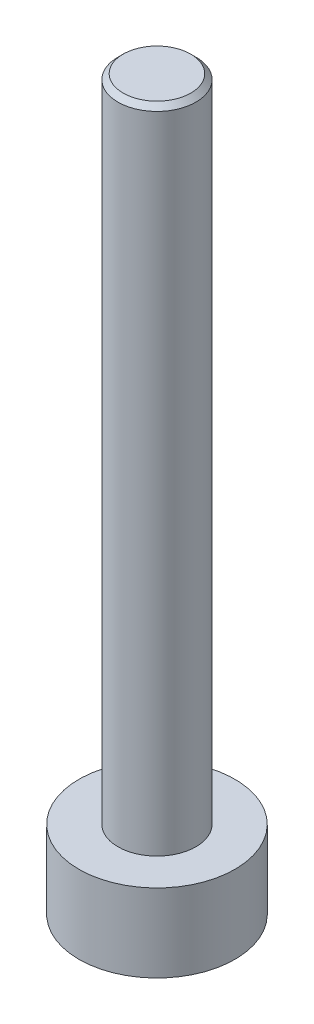
SolidWorks part; units mm, degrees
ref_plane "Front Plane" through (0, 0, 0) normal (0, 0, 1) x (1, 0, 0)
ref_plane "Top Plane" through (0, 0, 0) normal (0, 1, 0) x (1, 0, 0)
ref_plane "Right Plane" through (0, 0, 0) normal (1, 0, 0) x (0, 0, -1)
sketch "Sketch1" plane through (0, 0, 0) normal (0, 1, 0) x (1, 0, 0)
  circle A0 centre (0, 0) radius 3
  dimension "D1" = 6
extrude "Boss-Extrude1" add sketch "Sketch1" along normal blind 3
sketch "Sketch2" plane through (0, 3, 0) normal (0, 1, 0) x (1, 0, 0)
  circle A0 centre (0, 0) radius 1.5
  dimension "D1" = 3
extrude "Boss-Extrude2" add sketch "Sketch2" along normal blind 25 contours A0
chamfer "Chamfer1" distance 0.2 angle 45 1 edges at (0, 28, 1.5)
sketch "Sketch3" plane through (0, 0, 0) normal (0, -1, 0) x (1, 0, 0)
  line L1 (0, 1.5291) -> (-1.3242, 0.7646)
  line L2 (-1.3242, 0.7646) -> (-1.3242, -0.7646)
  line L3 (-1.3242, -0.7646) -> (0, -1.5291)
  line L4 (0, -1.5291) -> (1.3242, -0.7646)
  line L5 (1.3242, -0.7646) -> (1.3242, 0.7646)
  line L6 (1.3242, 0.7646) -> (0, 1.5291)
  circle A0 centre (0, 0) radius 1.3242 construction
extrude "Cut-Extrude1" cut sketch "Sketch3" against normal blind 2
